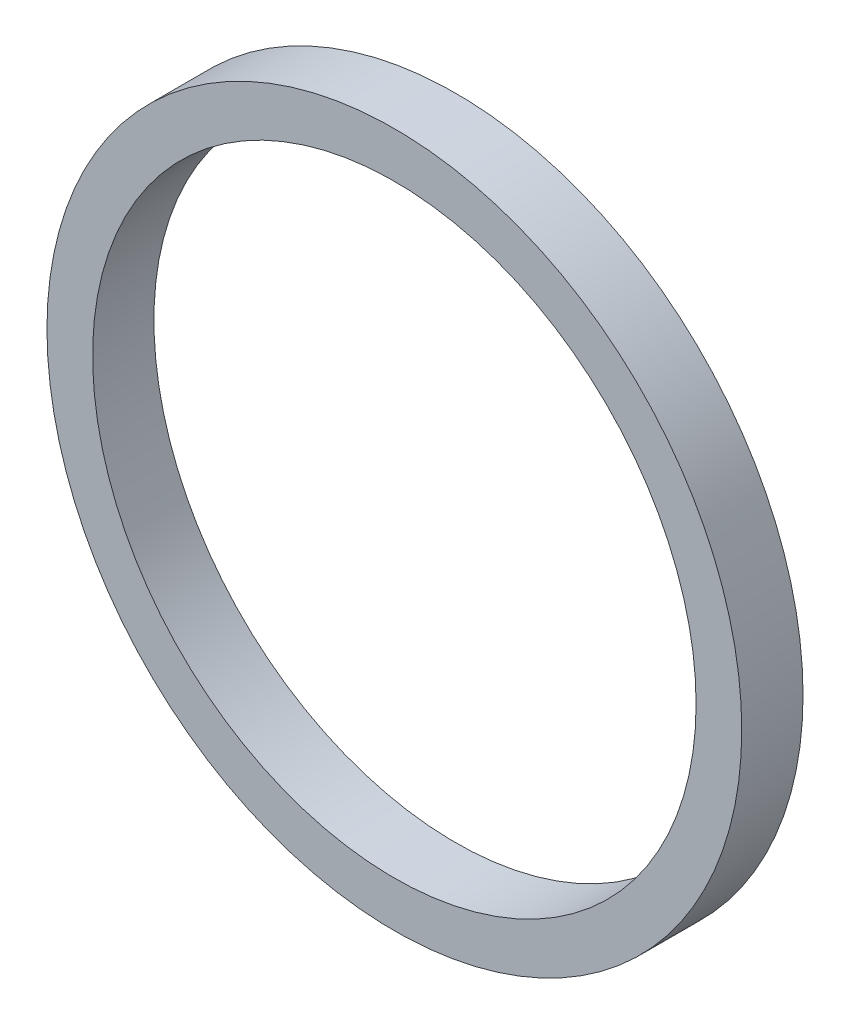
SolidWorks part; units mm, degrees
ref_plane "Front Plane" through (0, 0, 0) normal (0, 0, 1) x (1, 0, 0)
ref_plane "Top Plane" through (0, 0, 0) normal (0, 1, 0) x (1, 0, 0)
ref_plane "Right Plane" through (0, 0, 0) normal (1, 0, 0) x (0, 0, -1)
sketch "Sketch1" plane through (0, 0, 0) normal (0, 1, 0) x (1, 0, 0)
  line L0 (4.2479, 0.7588) -> (4.2479, 1.5081)
  line L1 (4.2479, 1.5081) -> (3.6896, 1.5081)
  line L2 (3.6896, 1.5081) -> (3.6896, 0.7588)
  line L3 (3.6896, 0.7588) -> (4.2479, 0.7588)
  line L4 (0, 1.5081) -> (0, 0.7588) construction
revolve "Revolve1" add sketch "Sketch1" angle 360 about L4
